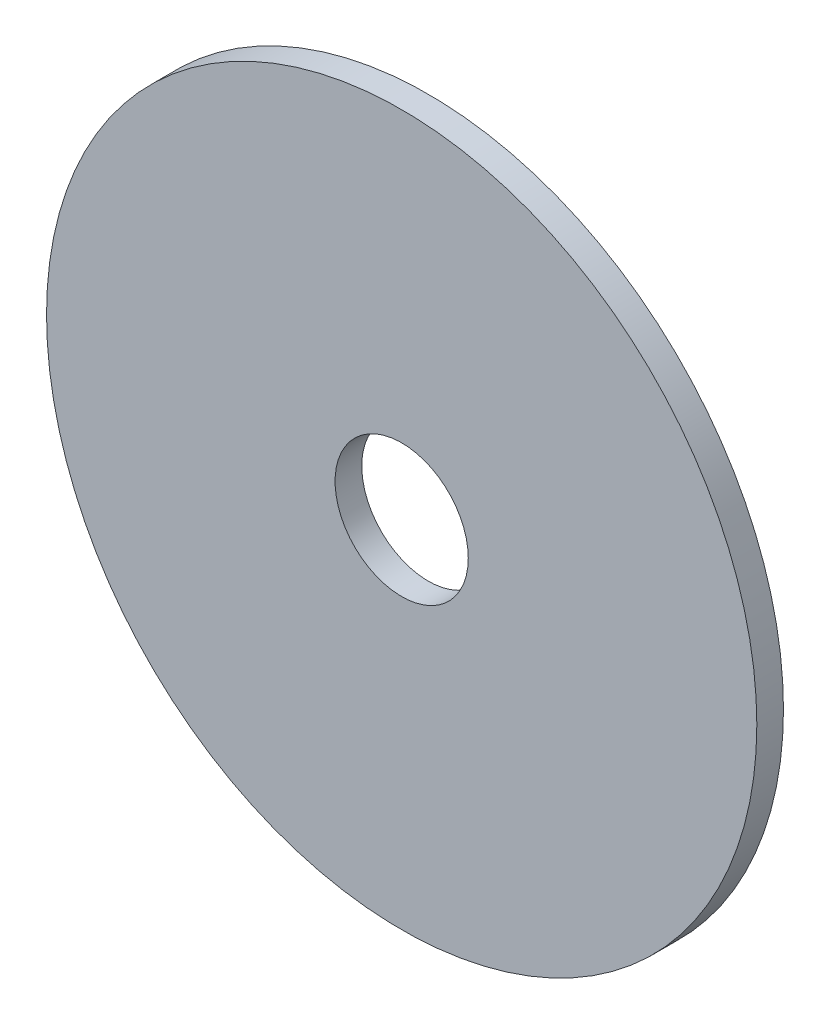
SolidWorks part; units mm, degrees
ref_plane "Front Plane" through (0, 0, 0) normal (0, 0, 1) x (1, 0, 0)
ref_plane "Top Plane" through (0, 0, 0) normal (0, 1, 0) x (1, 0, 0)
ref_plane "Right Plane" through (0, 0, 0) normal (1, 0, 0) x (0, 0, -1)
sketch "Sketch1" plane through (0, 0, 0) normal (0, 0, 1) x (1, 0, 0)
  circle A0 centre (0, 0) radius 4
  circle A1 centre (0, 0) radius 0.75
  dimension "D1" = 8
  dimension "D2" = 1.5
extrude "Boss-Extrude1" add sketch "Sketch1" along normal blind 0.3
